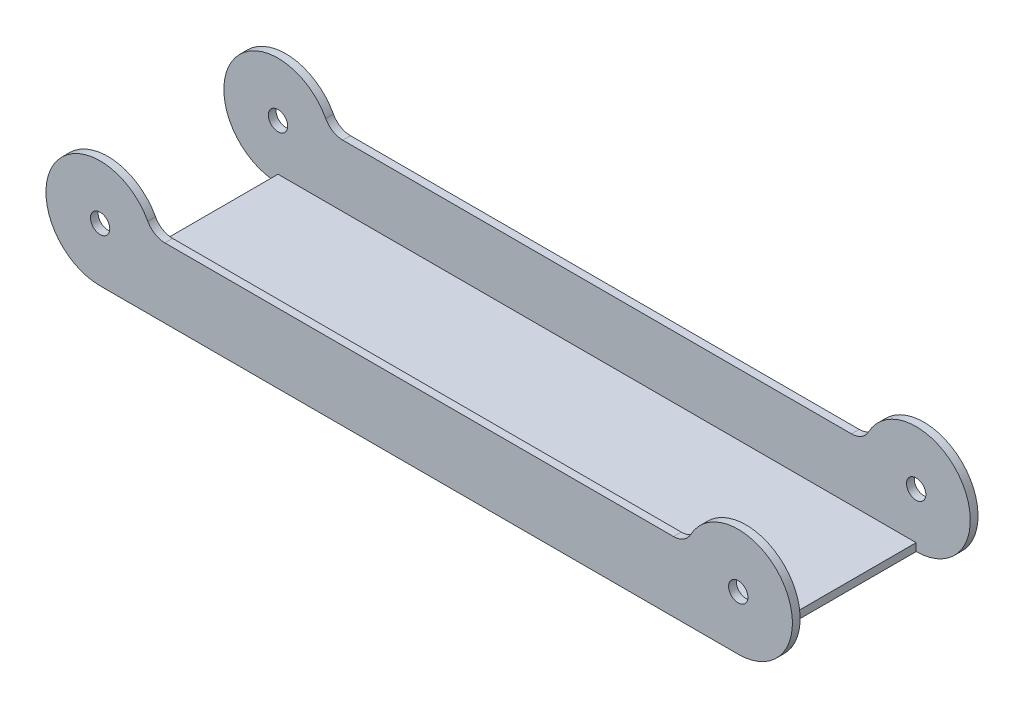
SolidWorks part; units mm, degrees
ref_plane "Front Plane" through (0, 0, 0) normal (0, 0, 1) x (1, 0, 0)
ref_plane "Top Plane" through (0, 0, 0) normal (0, 1, 0) x (1, 0, 0)
ref_plane "Right Plane" through (0, 0, 0) normal (1, 0, 0) x (0, 0, -1)
sketch "Sketch2" plane through (0, 0, 0) normal (0, 1, 0) x (1, 0, 0)
  line L1 (-97.5, 24) -> (97.5, 24)
  line L2 (-97.5, 24) -> (-97.5, -24)
  line L3 (-97.5, -24) -> (97.5, -24)
  line L4 (97.5, 24) -> (97.5, -24)
  line L5 (-97.5, 24) -> (97.5, -24) construction
  line L6 (-97.5, -24) -> (97.5, 24) construction
  point P0 (0, 0)
  dimension "D1" = 48
  dimension "D2" = 195
extrude "Boss-Extrude1" add sketch "Sketch2" along normal mid plane 28
shell "Shell1" thickness 2
sketch "Sketch3" plane through (0, 0, 24) normal (0, 0, 1) x (1, 0, 0)
  circle A0 centre (-82.5, 0) radius 2.5
  circle A1 centre (82.5, 0) radius 2.5
  dimension "D1" = 5
  dimension "D2" = 165
  dimension "D3" = 82.5
extrude "Cut-Extrude1" cut sketch "Sketch3" against normal through all
sketch "Sketch4" plane through (-95.5, 0, 0) normal (1, 0, 0) x (0, 0, -1)
  line L4 (-22, -12) -> (22, -12)
  line L5 (22, -12) -> (22, 14)
  line L6 (22, 14) -> (-22, 14)
  line L7 (-22, 14) -> (-22, -12)
  line L8 (-22, -12) -> (22, -12)
  line L9 (22, -12) -> (22, 14)
  line L10 (22, 14) -> (-22, 14)
  line L11 (-22, 14) -> (-22, -12)
  dimension "D1" = 0
extrude "Cut-Extrude2" cut sketch "Sketch4" against normal up to next and the other way up to next
sketch "Sketch6" plane through (0, 0, 0) normal (0, 0, 1) x (1, 0, 0)
  line L0 (-69.0836, 4) -> (69.0836, 4)
  line L1 (-97.5, 14) -> (97.5, 14) construction
  line L2 (97.5, 14) -> (97.5, -14) construction
  line L3 (-97.5, 14) -> (-97.5, -14) construction
  line L4 (-97.5, -14) -> (97.5, -14) construction
  line L5 (97.5, 24) -> (97.5, -14)
  line L7 (-97.5, 24) -> (-97.5, -14)
  line L8 (-97.5, -14) -> (-82.5, -14)
  line L9 (82.5, -14) -> (97.5, -14)
  line L10 (-97.5, 24) -> (97.5, 24)
  arc A0 (-69.0836, 4) -> (-82.5, -14) centre (-82.5, 0) ccw
  arc A1 (82.5, -14) -> (69.0836, 4) centre (82.5, 0) ccw
  dimension "D1" = 28
  dimension "D2" = 28
  dimension "D3" = 10
  dimension "D4" = 20
extrude "Cut-Extrude3" cut sketch "Sketch6" against normal through all both and the other way through all
sketch "Sketch7" plane through (0, -14, 0) normal (0, -1, 0) x (1, 0, 0)
  line L0 (82.5, -24) -> (82.5, 24) construction
  line L1 (89.7111, 22) -> (82.5, 22)
  line L2 (89.7111, 22) -> (89.7111, -22)
  line L3 (89.7111, -22) -> (82.5, -22)
  line L4 (82.5, 22) -> (82.5, -22)
  line L5 (-82.5, -24) -> (-82.5, 24) construction
  line L6 (-89.7111, 22) -> (-82.5, 22)
  line L7 (-89.7111, 22) -> (-89.7111, -22)
  line L8 (-89.7111, -22) -> (-82.5, -22)
  line L9 (-82.5, 22) -> (-82.5, -22)
extrude "Cut-Extrude4" cut sketch "Sketch7" against normal up to next
fillet "Fillet1" radius 5 4 edges at (69.0836, 4, -23) (69.0836, 4, 23) (-69.0836, 4, 23) (-69.0836, 4, -23)
